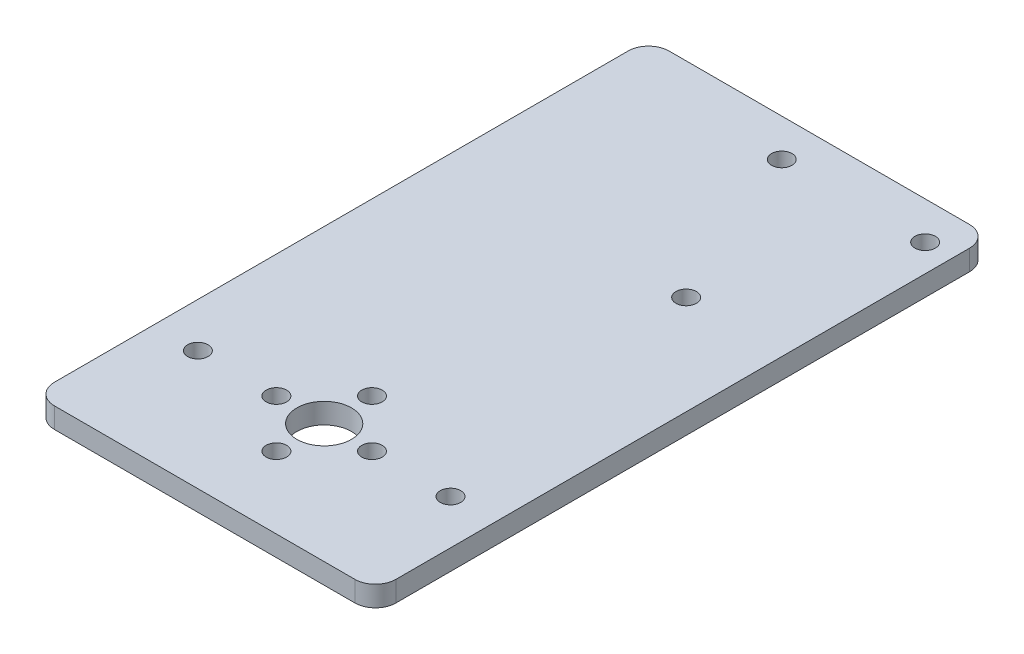
SolidWorks part; units mm, degrees
ref_plane "Front" through (0, 0, 0) normal (0, 0, 1) x (1, 0, 0)
ref_plane "Top" through (0, 0, 0) normal (0, 1, 0) x (1, 0, 0)
ref_plane "Right" through (0, 0, 0) normal (1, 0, 0) x (0, 0, -1)
sketch "草图1" plane through (0, 0, 0) normal (0, 1, 0) x (1, 0, 0)
  line L5 (25, 17.5) -> (25, -27.5)
  line L6 (25, -27.5) -> (-25, -27.5)
  line L8 (-25, 17.5) -> (-25, -27.5)
  line L10 (25, 17.5) -> (25, 62.5)
  line L11 (25, 62.5) -> (-25, 62.5)
  line L12 (-25, 62.5) -> (-25, 17.5)
  circle A15 centre (0, 57) radius 1.5
  circle A22 centre (10.5, 32.5) radius 1.5
  circle A25 centre (21, 57) radius 1.5
  circle A28 centre (0, -10) radius 4
  circle A30 centre (0, -3) radius 1.5
  circle A31 centre (-18.5, -10) radius 1.5
  circle A32 centre (18.5, -10) radius 1.5
  circle A33 centre (7, -10) radius 1.5
  circle A34 centre (0, -17) radius 1.5
  circle A35 centre (-7, -10) radius 1.5
  point P25 (0, -10)
  point P47 (0, 50)
  point P56 (10.5, 39.5)
  point P61 (21, 50)
  dimension "D2" = 4
extrude "凸台-拉伸1" add sketch "草图1" along normal blind 3
fillet "圆角2" radius 3 4 edges at (25, 1.5, 27.5) (-25, 1.5, 27.5) (25, 1.5, -62.5) (-25, 1.5, -62.5)
